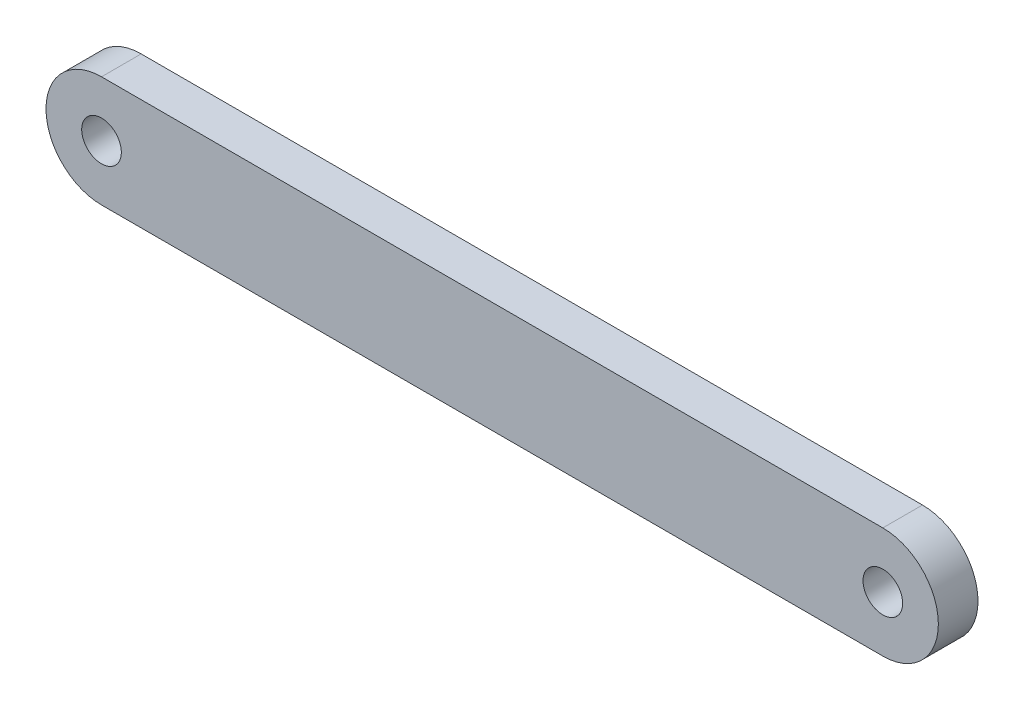
SolidWorks part; units mm, degrees
ref_plane "Front Plane" through (0, 0, 0) normal (0, 0, 1) x (1, 0, 0)
ref_plane "Top Plane" through (0, 0, 0) normal (0, 1, 0) x (1, 0, 0)
ref_plane "Right Plane" through (0, 0, 0) normal (1, 0, 0) x (0, 0, -1)
sketch "Sketch1" plane through (0, 0, 0) normal (0, 0, 1) x (1, 0, 0)
  line L0 (-49.911, -8.7733) -> (75.2094, -8.7733)
  line L1 (-49.911, 9.0067) -> (75.2094, 9.0067)
  line L2 (-49.911, -8.7733) -> (75.2094, 9.0067) construction
  line L3 (-49.911, 9.0067) -> (75.2094, -8.7733) construction
  arc A0 (-49.911, 9.0067) -> (-49.911, -8.7733) centre (-49.911, 0.1167) ccw
  arc A1 (75.2094, 9.0067) -> (75.2094, -8.7733) centre (75.2094, 0.1167) cw
  circle A2 centre (-49.911, 0.1167) radius 3.175
  circle A3 centre (75.2094, 0.1167) radius 3.175
  point P0 (12.6492, 0.1167)
  dimension "D3" = 6.35
  dimension "D1" = 125.1204
  dimension "D2" = 17.78
extrude "Boss-Extrude1" add sketch "Sketch1" along normal blind 6.35
